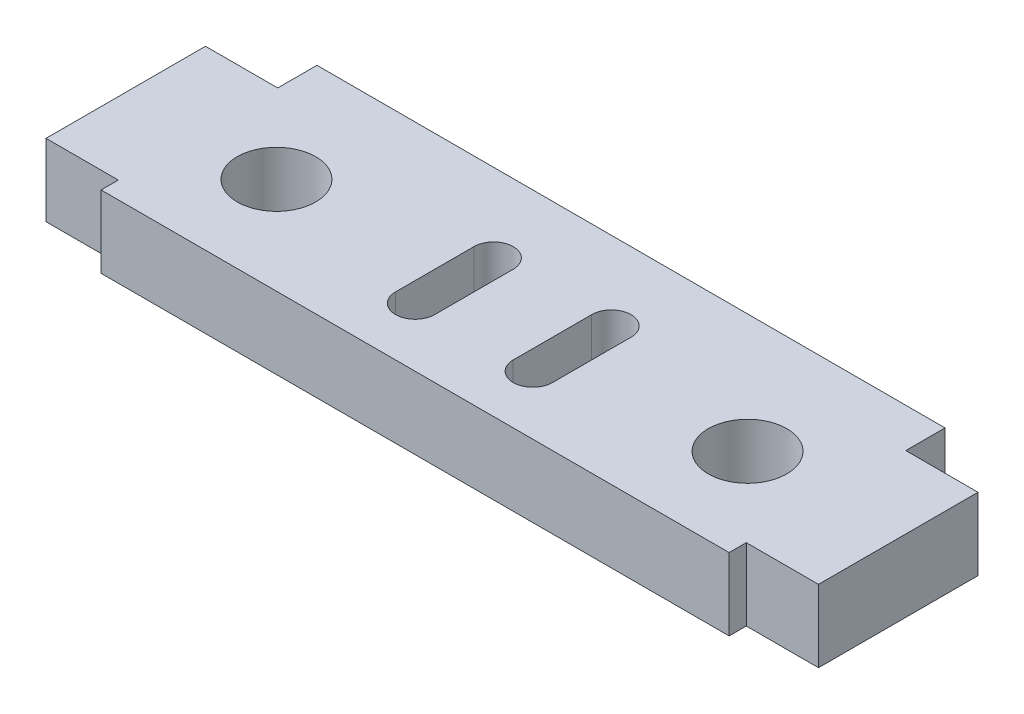
SolidWorks part; units mm, degrees
ref_plane "Front Plane" through (0, 0, 0) normal (0, 0, 1) x (1, 0, 0)
ref_plane "Top Plane" through (0, 0, 0) normal (0, 1, 0) x (1, 0, 0)
ref_plane "Right Plane" through (0, 0, 0) normal (1, 0, 0) x (0, 0, -1)
sketch "Sketch1" plane through (0, 0, 0) normal (0, 1, 0) x (1, 0, 0)
  line L0 (31.242, -6.45) -> (25.4, -6.45)
  line L1 (25.4, -7.8375) -> (-25.4, -7.8375)
  line L2 (25.4, -7.8375) -> (25.4, -6.45)
  line L3 (25.4, 8.0375) -> (-25.4, 8.0375)
  line L4 (-25.4, -7.8375) -> (-25.4, -6.45)
  line L5 (0, 8.0375) -> (0, -7.8375) construction
  line L6 (25.4, 0) -> (-25.4, 0) construction
  line L7 (-31.242, -6.45) -> (-25.4, -6.45)
  line L8 (-31.242, -6.45) -> (-31.242, 6.45)
  line L9 (-31.242, 6.45) -> (-25.4, 6.45)
  line L11 (-28.321, 6.45) -> (-28.321, -6.45) construction
  line L12 (-31.242, 0) -> (-25.4, 0) construction
  line L13 (31.242, 0) -> (25.4, 0) construction
  line L14 (31.242, -6.45) -> (31.242, 6.45)
  line L15 (31.242, 6.45) -> (25.4, 6.45)
  line L16 (28.321, 6.45) -> (28.321, -6.45) construction
  line L17 (25.4, 6.45) -> (25.4, 8.0375)
  line L18 (-25.4, 6.45) -> (-25.4, 8.0375)
  point P0 (0, 0)
  point P4 (-28.321, 0)
  dimension "D1" = 50.8
  dimension "D2" = 15.875
  dimension "D3" = 5.842
  dimension "D4" = 12.9
extrude "Boss-Extrude1" add sketch "Sketch1" along normal blind 5.842
sketch "Sketch2" plane through (0, 5.842, 0) normal (0, 1, 0) x (1, 0, 0)
  line L0 (0, 8.0375) -> (0, -7.8375) construction
  line L1 (25.4, 8.0375) -> (-25.4, 8.0375) construction
  line L2 (-25.4, -7.8375) -> (25.4, -7.8375) construction
  line L3 (31.242, 0) -> (-31.242, 0) construction
  line L4 (31.242, -6.45) -> (31.242, 6.45) construction
  line L5 (-31.242, 6.45) -> (-31.242, -6.45) construction
  circle A4 centre (-19.05, 0) radius 3.175
  circle A5 centre (19.05, 0) radius 3.175
  point P14 (-4.7625, 0)
  point P21 (4.7625, 0)
  dimension "D4" = 6.35
  dimension "D3" = 4.7625
  dimension "D5" = 19.05
extrude "Cut-Extrude1" cut sketch "Sketch2" against normal through all
sketch "Sketch3" [suppressed] plane through (0, 0, 0) normal (0, -1, 0) x (-1, 0, 0)
  line L0 (-31.242, 0) -> (31.242, 0) construction
  line L1 (-31.242, -6.35) -> (-31.242, 6.35) construction
  line L2 (31.242, 6.35) -> (31.242, -6.35) construction
  line L3 (-31.242, 3.175) -> (31.242, 3.175) construction
  line L4 (-3.175, 3.175) -> (3.175, 3.175) construction
  line L5 (-3.175, 4.7625) -> (3.175, 4.7625)
  line L6 (-3.175, 1.5875) -> (3.175, 1.5875)
  line L7 (-3.175, -3.175) -> (3.175, -3.175) construction
  line L8 (-3.175, -4.7625) -> (3.175, -4.7625)
  line L9 (-3.175, -1.5875) -> (3.175, -1.5875)
  arc A0 (-3.175, 4.7625) -> (-3.175, 1.5875) centre (-3.175, 3.175) ccw
  arc A1 (3.175, 1.5875) -> (3.175, 4.7625) centre (3.175, 3.175) ccw
  arc A2 (-3.175, -4.7625) -> (-3.175, -1.5875) centre (-3.175, -3.175) cw
  arc A3 (3.175, -1.5875) -> (3.175, -4.7625) centre (3.175, -3.175) cw
  point P10 (0, 3.175)
  point P17 (0, -3.175)
  dimension "D2" = 1.5875
  dimension "D1" = 3.175
  dimension "D3" = 6.35
extrude "Cut-Extrude2" [suppressed] cut sketch "Sketch3" against normal through all
sketch "Sketch4" plane through (0, 0, 0) normal (0, -1, 0) x (-1, 0, 0)
  line L0 (0, 8.0375) -> (0, -7.8375) construction
  line L1 (-25.4, 8.0375) -> (25.4, 8.0375) construction
  line L2 (25.4, -7.8375) -> (-25.4, -7.8375) construction
  line L3 (4.7625, 8.0375) -> (4.7625, -7.8375) construction
  line L4 (4.7625, -3.075) -> (4.7625, 3.275) construction
  line L5 (3.175, -3.075) -> (3.175, 3.275)
  line L6 (6.35, -3.075) -> (6.35, 3.275)
  line L7 (-4.7625, -3.075) -> (-4.7625, 3.275) construction
  line L8 (-3.175, -3.075) -> (-3.175, 3.275)
  line L9 (-6.35, -3.075) -> (-6.35, 3.275)
  arc A0 (3.175, -3.075) -> (6.35, -3.075) centre (4.7625, -3.075) ccw
  arc A1 (6.35, 3.275) -> (3.175, 3.275) centre (4.7625, 3.275) ccw
  arc A2 (-3.175, -3.075) -> (-6.35, -3.075) centre (-4.7625, -3.075) cw
  arc A3 (-6.35, 3.275) -> (-3.175, 3.275) centre (-4.7625, 3.275) cw
  point P10 (4.7625, 0.1)
  point P17 (-4.7625, 0.1)
  dimension "D2" = 1.5875
  dimension "D1" = 6.35
  dimension "D3" = 4.7625
extrude "Cut-Extrude3" cut sketch "Sketch4" against normal through all
sketch "Sketch5" plane through (0, 0, 0) normal (0, -1, 0) x (-1, 0, 0)
  line L0 (0, 0) -> (31.242, 0) construction
  line L1 (-25.4, 8.0375) -> (25.4, 8.0375)
  line L2 (-25.4, 8.0375) -> (-25.4, 9.625)
  line L3 (-25.4, 9.625) -> (25.4, 9.625)
  line L4 (25.4, 8.0375) -> (25.4, 9.625)
  line L5 (-25.4, 8.0375) -> (25.4, 9.625) construction
  line L6 (-25.4, 9.625) -> (25.4, 8.0375) construction
  line L9 (25.4, 8.0375) -> (25.4, 6.45) construction
  line L10 (31.242, 6.45) -> (31.242, -6.45) construction
  point P4 (0, 8.8313)
  dimension "D1" = 1.5875
extrude "Boss-Extrude2" add sketch "Sketch5" against normal up to surface (5.842 mm away) up to face at (4.7625, 5.842, -0.1)
